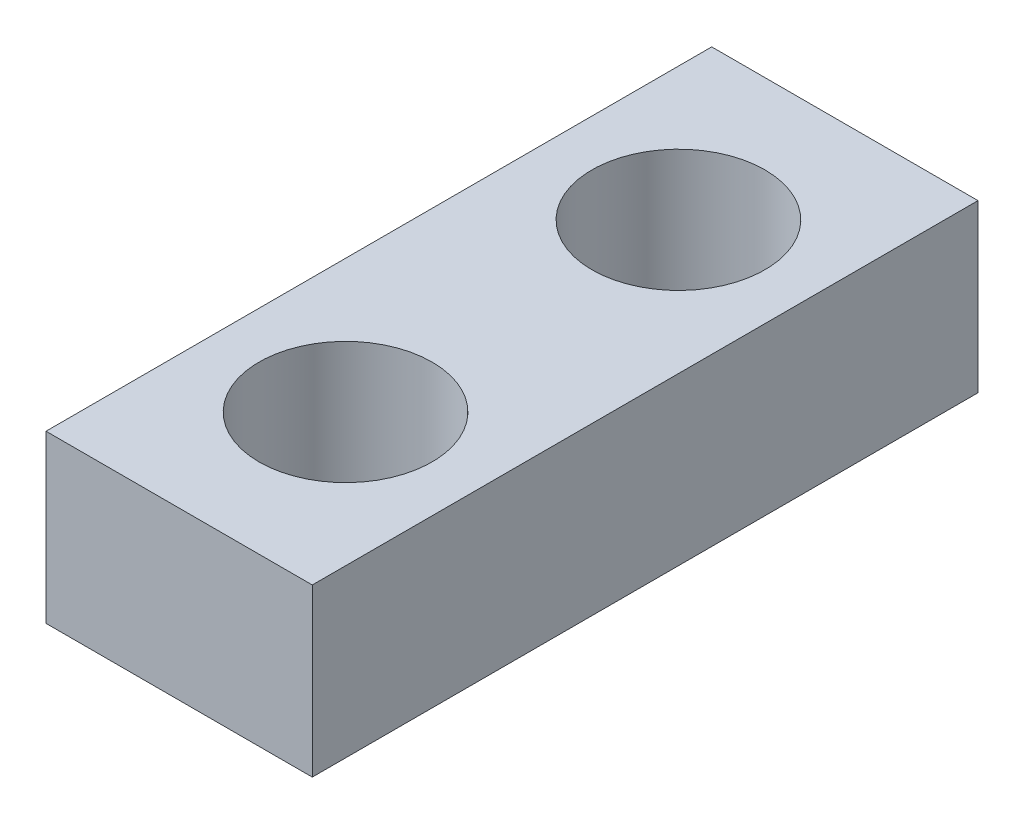
SolidWorks part; units mm, degrees
ref_plane "Front Plane" through (0, 0, 0) normal (0, 0, 1) x (1, 0, 0)
ref_plane "Top Plane" through (0, 0, 0) normal (0, 1, 0) x (1, 0, 0)
ref_plane "Right Plane" through (0, 0, 0) normal (1, 0, 0) x (0, 0, -1)
sketch "Sketch1" plane through (0, 0, 0) normal (0, 1, 0) x (1, 0, 0)
  line L0 (0, 0) -> (10.16, 0)
  line L1 (0, 0) -> (0, 25.4)
  line L2 (10.16, 0) -> (10.16, 25.4)
  line L3 (0, 25.4) -> (10.16, 25.4)
  line L4 (5.08, 0) -> (5.08, 6.35) construction
  line L5 (5.08, 25.4) -> (5.08, 19.05) construction
  circle A0 centre (5.08, 6.35) radius 3.302
  circle A1 centre (5.08, 19.05) radius 3.302
extrude "Boss-Extrude1" add sketch "Sketch1" along normal blind 6.35 contours L3 L2 L0 L1
